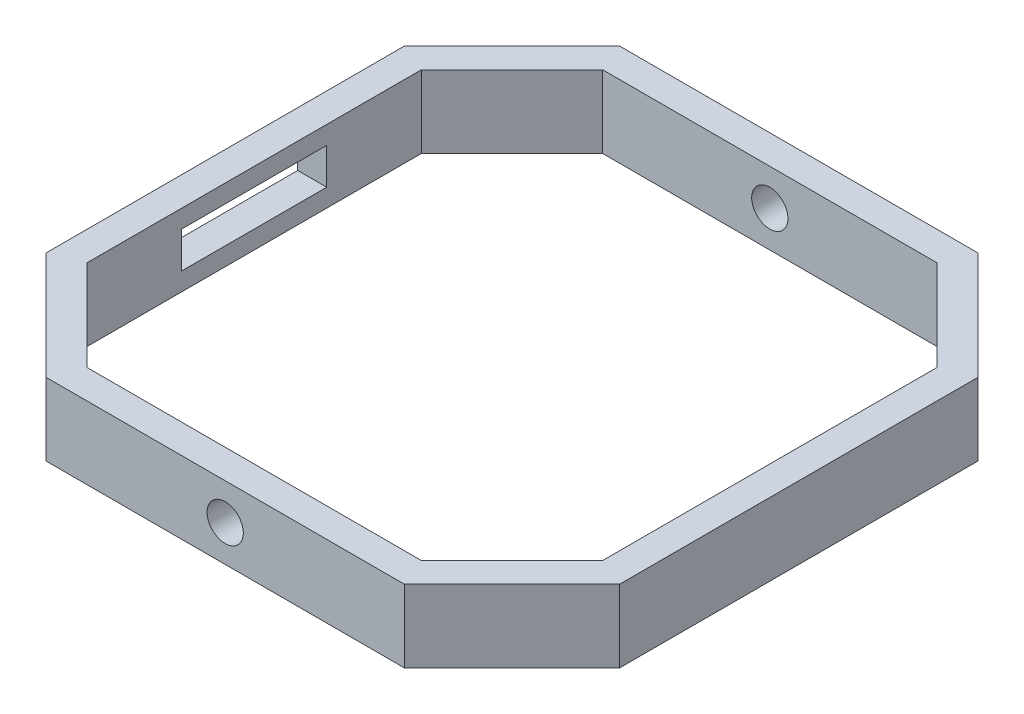
SolidWorks part; units mm, degrees
ref_plane "Front Plane" through (0, 0, 0) normal (0, 0, 1) x (1, 0, 0)
ref_plane "Top Plane" through (0, 0, 0) normal (0, 1, 0) x (1, 0, 0)
ref_plane "Right Plane" through (0, 0, 0) normal (1, 0, 0) x (0, 0, -1)
sketch "Sketch1" plane through (0, 0, 0) normal (0, 1, 0) x (1, 0, 0)
  line L0 (-35.55, 23.05) -> (-23.05, 35.55)
  line L1 (-23.05, -35.55) -> (23.05, -35.55)
  line L2 (-35.55, -23.05) -> (-35.55, 23.05)
  line L3 (-23.05, 35.55) -> (23.05, 35.55)
  line L4 (35.55, -23.05) -> (35.55, 23.05)
  line L5 (-35.55, -35.55) -> (35.55, 35.55) construction
  line L6 (-35.55, 35.55) -> (35.55, -35.55) construction
  line L7 (23.05, 35.55) -> (35.55, 23.05)
  line L8 (23.05, -35.55) -> (35.55, -23.05)
  line L9 (-35.55, -23.05) -> (-23.05, -35.55)
  line L18 (-24.7069, 39.55) -> (24.7069, 39.55)
  line L19 (24.7069, 39.55) -> (39.55, 24.7069)
  line L20 (39.55, -24.7069) -> (39.55, 24.7069)
  line L21 (24.7069, -39.55) -> (39.55, -24.7069)
  line L22 (-24.7069, -39.55) -> (24.7069, -39.55)
  line L23 (-39.55, -24.7069) -> (-24.7069, -39.55)
  line L24 (-39.55, -24.7069) -> (-39.55, 24.7069)
  line L25 (-39.55, 24.7069) -> (-24.7069, 39.55)
  point P0 (0, 0)
  dimension "D1" = 71.1
  dimension "D2" = 71.1
  dimension "D3" = 4
extrude "Boss-Extrude1" add sketch "Sketch1" along normal mid plane 10
sketch "Sketch3" plane through (39.55, 0, 0) normal (1, 0, 0) x (0, 0, -1)
  line L1 (-10, -2.5) -> (10, -2.5)
  line L2 (-10, -2.5) -> (-10, 2.5)
  line L3 (-10, 2.5) -> (10, 2.5)
  line L4 (10, -2.5) -> (10, 2.5)
  line L5 (-10, -2.5) -> (10, 2.5) construction
  line L6 (-10, 2.5) -> (10, -2.5) construction
  point P0 (0, 0)
  dimension "D1" = 20
  dimension "D2" = 5
extrude "Cut-Extrude2" cut sketch "Sketch3" against normal through all from surface at -75.1 starting at face at (-35.55, 0, 0)
sketch "Sketch4" plane through (0, 0, -39.55) normal (0, 0, -1) x (-1, 0, 0)
  circle A0 centre (0, 0) radius 2.5
  dimension "D1" = 5
extrude "Cut-Extrude3" cut sketch "Sketch4" against normal through all both and the other way through all
